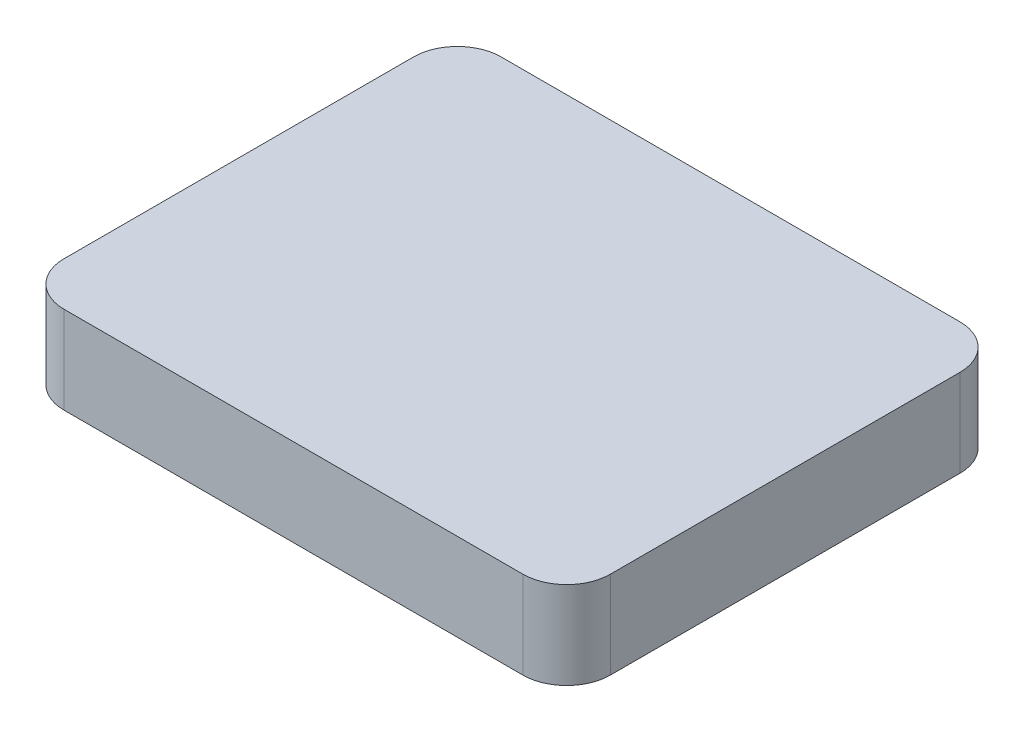
SolidWorks part; units mm, degrees
material "Teak"
ref_plane "Front Plane" through (0, 0, 0) normal (0, 0, 1) x (1, 0, 0)
ref_plane "Top Plane" through (0, 0, 0) normal (0, 1, 0) x (1, 0, 0)
ref_plane "Right Plane" through (0, 0, 0) normal (1, 0, 0) x (0, 0, -1)
sketch "Sketch3" plane through (0, 0, 0) normal (0, 1, 0) x (1, 0, 0)
  line L1 (-105, 100) -> (105, 100)
  line L2 (-125, 80) -> (-125, -80)
  line L3 (-105, -100) -> (105, -100)
  line L4 (125, 80) -> (125, -80)
  arc A0 (-125, -80) -> (-105, -100) centre (-105, -80) ccw
  arc A1 (125, -80) -> (105, -100) centre (105, -80) cw
  arc A2 (125, 80) -> (105, 100) centre (105, 80) ccw
  arc A3 (-105, 100) -> (-125, 80) centre (-105, 80) ccw
  point P0 (0, 0)
  point P10 (125, -100)
  point P13 (125, 100)
  point P16 (-125, 100)
  dimension "D5" = 20
  dimension "D1" = 250
  dimension "D2" = 125
  dimension "D3" = 200
  dimension "D4" = 100
extrude "Boss-Extrude2" add sketch "Sketch3" along normal blind 40 contours L1 A2 L4 A1 L3 A0 L2 A3
